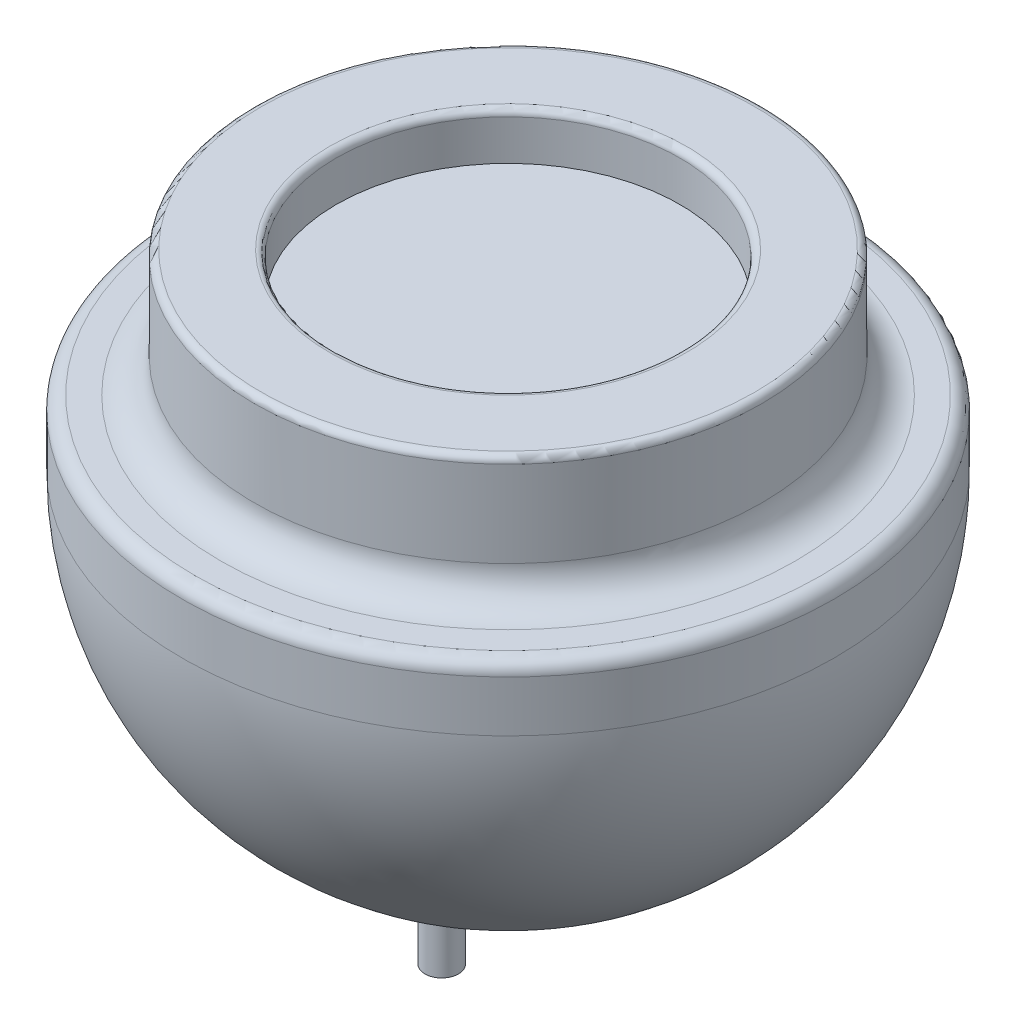
SolidWorks part; units mm, degrees
ref_plane "Front Plane" through (0, 0, 0) normal (0, 0, 1) x (1, 0, 0)
ref_plane "Top Plane" through (0, 0, 0) normal (0, 1, 0) x (1, 0, 0)
ref_plane "Right Plane" through (0, 0, 0) normal (1, 0, 0) x (0, 0, -1)
sketch "Sketch1" plane through (0, 0, 0) normal (0, 0, 1) x (1, 0, 0)
  line L0 (0, -1000) -> (0, 49000) construction
  line L1 (0, 0) -> (486, 0) construction
  line L2 (0, 214) -> (256, 214)
  line L3 (256, 214) -> (256, 284)
  line L4 (256, 284) -> (378, 284)
  line L5 (378, 284) -> (378, 146)
  line L6 (174, -453.7841) -> (0, -453.7841)
  line L7 (0, 214) -> (0, -453.7841)
  line L8 (486, 0) -> (486, 76)
  line L9 (466, 96) -> (428, 96)
  arc A0 (174, -453.7841) -> (486, 0) centre (0, 0) ccw
  arc A1 (378, 146) -> (428, 96) centre (428, 146) ccw
  arc A2 (466, 96) -> (486, 76) centre (466, 76) cw
  dimension "D1" = 50
  dimension "D2" = 20
  dimension "D6" = 486
  dimension "D3" = 256
  dimension "D4" = 122
  dimension "D5" = 138
  dimension "D7" = 174
  dimension "D8" = 70
  dimension "D9" = 76
revolve "Revolve1" add sketch "Sketch1" angle 360 about L0
fillet "Fillet1" radius 10 2 edges at (256, 284, 0) (378, 284, 0)
sketch "Sketch2" plane through (0, -453.7841, 0) normal (0, -1, 0) x (1, 0, 0)
  line L0 (-1000, 0) -> (49000, 0) construction
  circle A0 centre (-270, 0) radius 25
  circle A1 centre (0, 0) radius 174 construction
  point P4 (-300, 0)
  dimension "D1" = 270
  dimension "D2" = 50
extrude "Boss-Extrude1" add sketch "Sketch2" against normal blind 80
sketch "Sketch3" plane through (0, 0, 0) normal (1, 0, 0) x (0, 0, -1)
  line L0 (0, -1000) -> (0, 49000) construction
pattern_circular "CirPattern1" count 3 over 360 about axis through (0, 0, 0) along (0, 1, 0) of "Boss-Extrude1"
